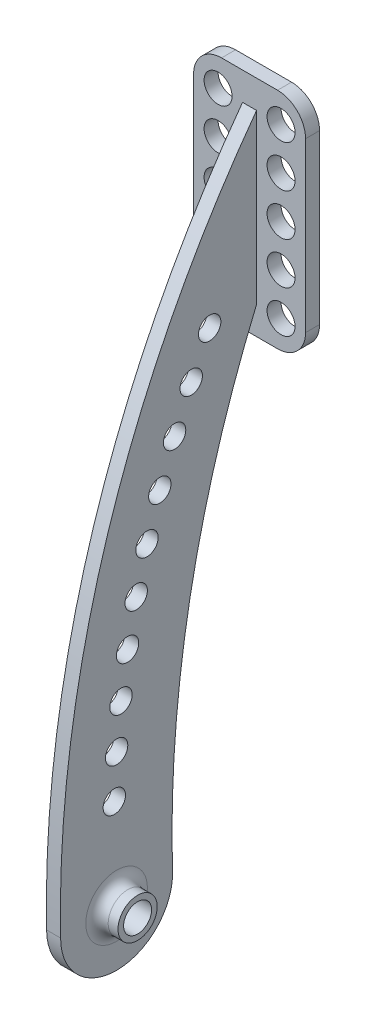
SolidWorks part; units mm, degrees
ref_plane "Front Plane" through (0, 0, 0) normal (0, 0, 1) x (1, 0, 0)
ref_plane "Top Plane" through (0, 0, 0) normal (0, 1, 0) x (1, 0, 0)
ref_plane "Right Plane" through (0, 0, 0) normal (1, 0, 0) x (0, 0, -1)
sketch "Sketch1" plane through (0, 0, 0) normal (1, 0, 0) x (0, 0, -1)
  line L0 (0, 0) -> (0, 47.625) construction
  line L1 (0, 47.625) -> (0, 191.0514) construction
  line L2 (0, 191.0514) -> (50, 191.0514) construction
  line L3 (-20, 0) -> (-20, 190.5) construction
  line L5 (50, 221.0514) -> (50, 161.0514)
  circle A0 centre (0, 0) radius 5
  circle A1 centre (0, 47.625) radius 4
  arc A2 (-20, 0) -> (20, 0) centre (0, 0) ccw
  arc A3 (50, 161.0514) -> (20, 0) centre (399.7919, 12.5738) ccw
  arc A4 (50, 221.0514) -> (-20, 0) centre (339.919, 7.6341) ccw
  circle A5 centre (1.5734, 62.5422) radius 4
  circle A6 centre (3.9128, 77.3587) radius 4
  circle A7 centre (7.0132, 92.0348) radius 4
  circle A8 centre (10.8616, 106.5327) radius 4
  circle A9 centre (15.4379, 120.8176) radius 4
  circle A10 centre (20.7151, 134.8586) radius 4
  circle A11 centre (26.6615, 148.6296) radius 4
  circle A12 centre (33.2411, 162.1096) radius 4
  circle A13 centre (-0.8107, 32.6469) radius 4
  spline S0 degree 2 poles (50, 191.0514) (-7.8386, 101.0856) (0, 0) knots 0 0 0 1 1 1 construction
  spline S1 degree 2 poles (50, 221.0514) (-43.1566, 125.6164) (-20, 0) knots 0 0 0 1 1 1 construction
  spline S2 degree 2 poles (50, 221.0514) (-17.3239, 120.9323) (-20, 0) knots 0 0 0 1 1 1 construction
  point P15 (50, 191.0514)
  dimension "D1" = 60
  dimension "D2" = 8
  dimension "D3" = 10
  dimension "D4" = 8
  dimension "D5" = 15
  dimension "D6" = 15
  dimension "D7" = 15
  dimension "D8" = 15
  dimension "D9" = 15
  dimension "D10" = 15
  dimension "D11" = 15
  dimension "D12" = 15
  dimension "D13" = 15
extrude "Boss-Extrude1" add sketch "Sketch1" along normal blind 5
sketch "Sketch2" plane through (5, 0, 0) normal (1, 0, 0) x (0, 0, -1)
  circle A0 centre (0, 0) radius 7
  circle A1 centre (0, 0) radius 5 construction
  circle A2 centre (0, 0) radius 5
extrude "Boss-Extrude3" add sketch "Sketch2" along normal blind 7.5 and the other way blind 12.5
sketch "Sketch3" plane through (0, 0, -50) normal (0, 0, -1) x (-1, 0, 0)
  line L0 (-5, 161.0514) -> (-5, 221.0514) construction
  line L1 (-12.5, 151.0514) -> (7.5, 151.0514)
  line L2 (-22.5, 161.0514) -> (-22.5, 221.0514)
  line L3 (-12.5, 231.0514) -> (7.5, 231.0514)
  line L4 (17.5, 161.0514) -> (17.5, 221.0514)
  line L5 (-22.5, 151.0514) -> (17.5, 231.0514) construction
  line L6 (-22.5, 231.0514) -> (17.5, 151.0514) construction
  line L7 (-2.5, 231.0514) -> (-2.5, 151.0514) construction
  line L8 (17.5, 191.0514) -> (-22.5, 191.0514) construction
  line L10 (-5, 161.0514) -> (0, 161.0514) construction
  circle A0 centre (-13.75, 221.0514) radius 5
  circle A1 centre (-13.75, 206.0514) radius 5
  circle A2 centre (-13.75, 191.0514) radius 5
  circle A3 centre (-13.75, 161.0514) radius 5
  circle A4 centre (-13.75, 176.0514) radius 5
  circle A5 centre (8.75, 161.0514) radius 5
  circle A6 centre (8.75, 176.0514) radius 5
  circle A7 centre (8.75, 191.0514) radius 5
  circle A8 centre (8.75, 206.0514) radius 5
  circle A9 centre (8.75, 221.0514) radius 5
  arc A10 (-12.5, 151.0514) -> (-22.5, 161.0514) centre (-12.5, 161.0514) cw
  arc A11 (7.5, 151.0514) -> (17.5, 161.0514) centre (7.5, 161.0514) ccw
  arc A12 (7.5, 231.0514) -> (17.5, 221.0514) centre (7.5, 221.0514) cw
  arc A13 (-22.5, 221.0514) -> (-12.5, 231.0514) centre (-12.5, 221.0514) cw
  point P0 (-2.5, 191.0514)
  dimension "D3" = 10
  dimension "D7" = 10
  dimension "D1" = 2.5
  dimension "D2" = 30
  dimension "D4" = 15
  dimension "D5" = 15
  dimension "D6" = 8.75
  dimension "D8" = 80
  dimension "D9" = 40
extrude "Boss-Extrude4" add sketch "Sketch3" along normal blind 5
fillet "Fillet1" radius 4 2 edges at (0, 0, -7) (5, 0, -7)
